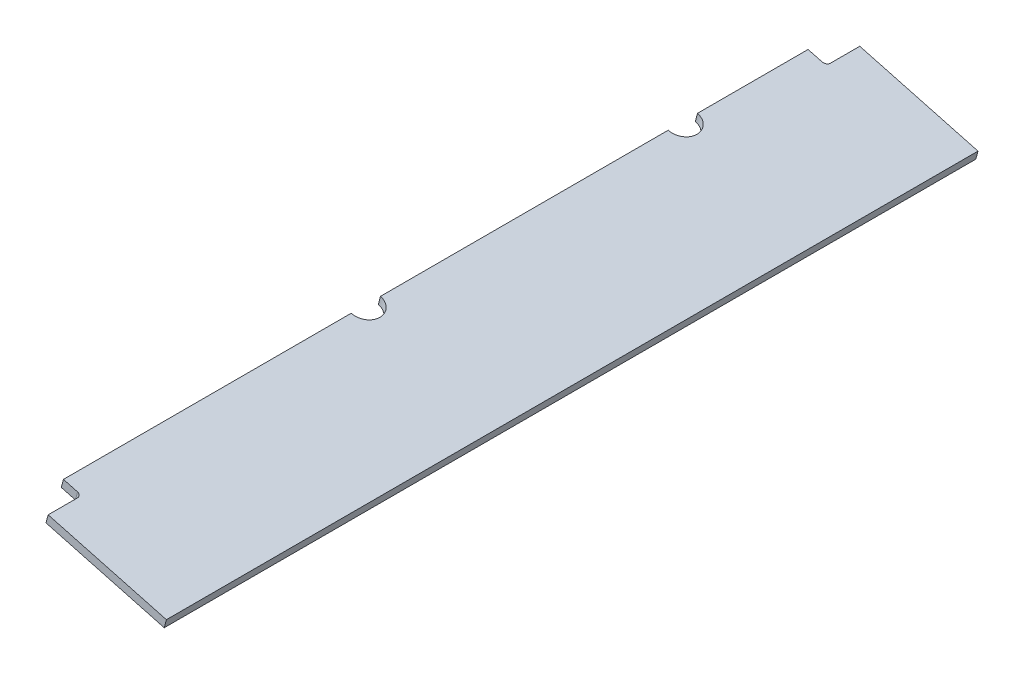
SolidWorks part; units mm, degrees
material "PE High Density"
ref_plane "Front Plane" through (0, 0, 0) normal (0, 0, 1) x (1, 0, 0)
ref_plane "Top Plane" through (0, 0, 0) normal (0, 1, 0) x (1, 0, 0)
ref_plane "Right Plane" through (0, 0, 0) normal (1, 0, 0) x (0, 0, -1)
sketch "Sketch1" plane through (0, 0, 0) normal (0, 0, 1) x (1, 0, 0)
  line L12 (232.6545, 12.2673) -> (25.6446, 67.7354)
  line L13 (25.6446, 67.7354) -> (22.3576, 55.4682)
  line L14 (229.3675, 0) -> (232.6545, 12.2673)
  line L19 (229.3675, 0) -> (22.3576, 55.4682)
  dimension "D2" = 214.3125
  dimension "D7" = 12.7
extrude "Boss-Extrude1" add sketch "Sketch1" along normal blind 1231.392
sketch "Sketch5" plane through (18.6517, 69.6091, 0) normal (0.2588, 0.9659, 0) x (0.9659, -0.2588, 0)
  line L11 (221.552, -1231.392) -> (7.2395, -1231.392) construction
  line L19 (7.2395, -1231.392) -> (7.2395, 0) construction
  line L20 (7.2395, -1231.392) -> (35.8145, -1231.392)
  line L21 (7.2395, -1231.392) -> (7.2395, -1180.592)
  line L22 (7.2395, -1180.592) -> (35.8145, -1180.592)
  line L23 (35.8145, -1231.392) -> (35.8145, -1180.592)
  line L24 (7.2395, -1231.392) -> (35.8145, -1180.592) construction
  line L25 (7.2395, -1180.592) -> (35.8145, -1231.392) construction
  line L27 (7.2395, 0) -> (35.8145, 0)
  line L28 (7.2395, 0) -> (7.2395, -50.8)
  line L29 (7.2395, -50.8) -> (35.8145, -50.8)
  line L30 (35.8145, 0) -> (35.8145, -50.8)
  line L31 (7.2395, 0) -> (35.8145, -50.8) construction
  line L32 (7.2395, -50.8) -> (35.8145, 0) construction
  circle A1 centre (7.2395, -721.8045) radius 22.225
  circle A2 centre (7.2395, -240.792) radius 22.225
  point P7 (21.527, -1205.992)
  point P14 (21.527, -25.4)
  point P17 (21.527, -1180.592)
  dimension "D4" = 44.45
  dimension "D5" = 481.0125
  dimension "D1" = 28.575
  dimension "D2" = 50.8
  dimension "D3" = 458.7875
extrude "Cut-Extrude2" cut sketch "Sketch5" against normal through all
fillet "Fillet1" radius 6.35 2 edges at (51.6024, 54.206, 50.8) (51.6024, 54.206, 1180.592)
